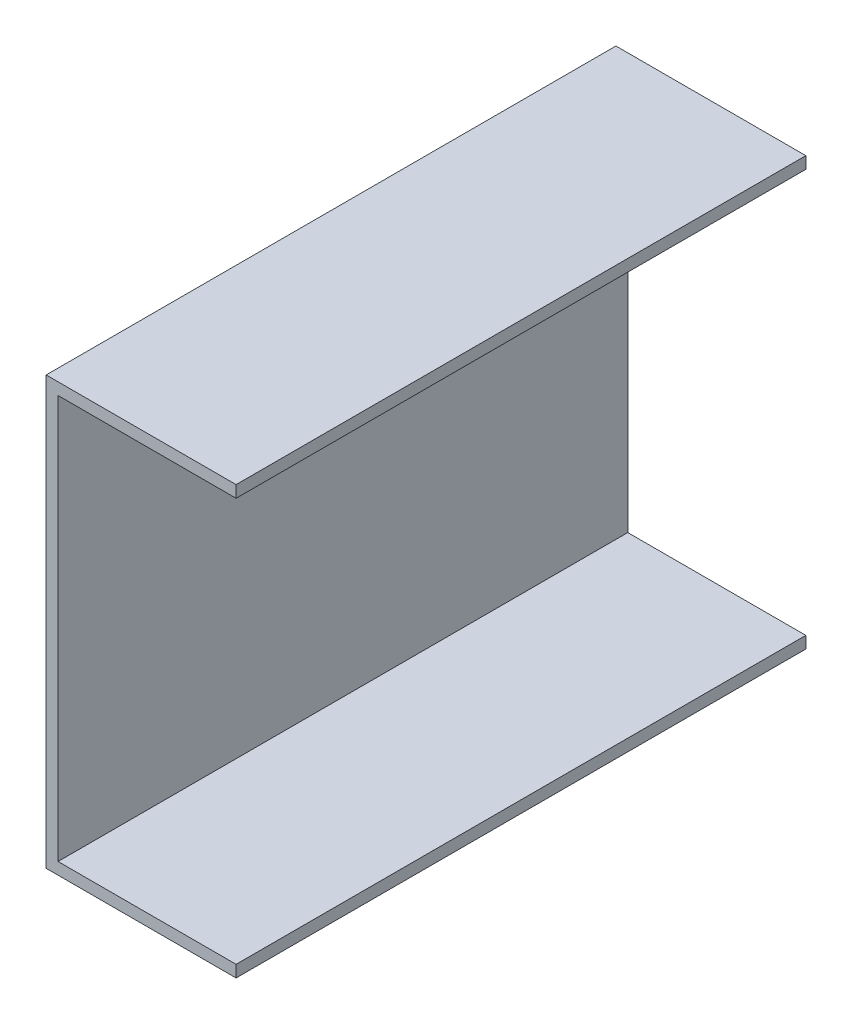
SolidWorks part; units mm, degrees
ref_plane "Front Plane" through (0, 0, 0) normal (0, 0, 1) x (1, 0, 0)
ref_plane "Top Plane" through (0, 0, 0) normal (0, 1, 0) x (1, 0, 0)
ref_plane "Right Plane" through (0, 0, 0) normal (1, 0, 0) x (0, 0, -1)
sketch "Sketch1" plane through (0, 0, 0) normal (0, 0, 1) x (1, 0, 0)
  line L0 (0, 0) -> (-25.4, 0)
  line L1 (-25.4, 0) -> (-25.4, -57.15)
  line L2 (-25.4, -57.15) -> (0, -57.15)
  dimension "D1" = 57.15
  dimension "D2" = 25.4
  dimension "D3" = 25.4
extrude "Extrude-Thin1" add sketch "Sketch1" along normal blind 76.2 thin thin type one direction reverse wall 1.5875
